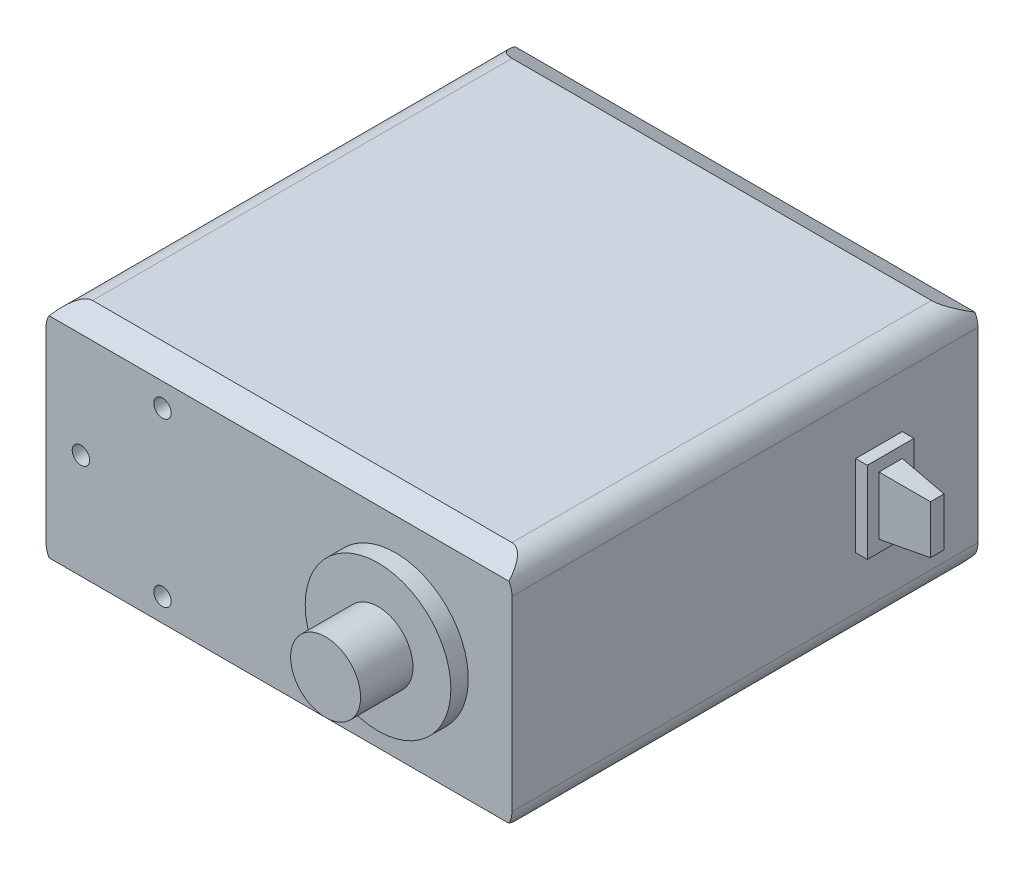
SolidWorks part; units mm, degrees
ref_plane "Спереди" through (0, 0, 0) normal (0, 0, 1) x (1, 0, 0)
ref_plane "Сверху" through (0, 0, 0) normal (0, 1, 0) x (1, 0, 0)
ref_plane "Справа" through (0, 0, 0) normal (1, 0, 0) x (0, 0, -1)
sketch "Эскиз1" plane through (0, 0, 0) normal (0, 1, 0) x (1, 0, 0)
  line L0 (0, 0) -> (40, 0)
  line L1 (40, 0) -> (40, -40)
  line L2 (40, -40) -> (0, -40)
  line L3 (0, -40) -> (0, 0)
extrude "Бобышка-Вытянуть1" add sketch "Эскиз1" along normal blind 20
sketch "Эскиз2" plane through (0, 0, 40) normal (0, 0, 1) x (1, 0, 0)
  line L0 (40, 10) -> (36.25, 10) construction
  line L1 (40, 20) -> (40, 0) construction
  line L2 (0, 10) -> (23.75, 10) construction
  line L3 (0, 20) -> (0, 0) construction
  line L4 (36.25, 10) -> (23.75, 10) construction
  circle A0 centre (30, 10) radius 6.25
  dimension "D1" = 12.5
  dimension "D2" = 3.75
extrude "Бобышка-Вытянуть2" add sketch "Эскиз2" along normal blind 1.5
sketch "Эскиз3" plane through (0, 0, 41.5) normal (0, 0, 1) x (1, 0, 0)
  circle A0 centre (30, 10) radius 3
extrude "Шестерня" add sketch "Эскиз3" along normal blind 4.5
sketch "Эскиз4" plane through (0, 0, 0) normal (0, 0, -1) x (-1, 0, 0)
  circle A0 centre (-30, 10) radius 6.25
extrude "Бобышка-Вытянуть4" add sketch "Эскиз4" along normal blind 1.5
sketch "Эскиз5" plane through (0, 0, -1.5) normal (0, 0, -1) x (-1, 0, 0)
  circle A0 centre (-30, 10) radius 3
extrude "Бобышка-Вытянуть5" add sketch "Эскиз5" along normal blind 3.7
sketch "Эскиз7" plane through (0, 0, 0) normal (0, 0, -1) x (-1, 0, 0)
  line L0 (0, 20) -> (-20, 0) construction
  line L1 (-40, 0) -> (0, 0) construction
  line L2 (0, 0) -> (-20, 20) construction
  line L3 (-40, 20) -> (0, 20) construction
  line L4 (0, 10.2204) -> (-2.5, 10.2204) construction
  line L5 (0, 20) -> (0, 0) construction
  line L6 (-2.5, 10.2204) -> (-2.5, 17.5) construction
  line L7 (-2.5, 10.2204) -> (-2.5, 2.5) construction
  line L8 (-2.5, 2.5) -> (-17.5, 2.5) construction
  line L9 (-17.5, 2.5) -> (-17.5, 17.5) construction
  line L10 (-17.5, 17.5) -> (-2.5, 17.5) construction
  circle A0 centre (-17.5, 17.5) radius 0.75
  circle A1 centre (-2.5, 17.5) radius 0.75
  circle A2 centre (-2.5, 2.5) radius 0.75
  circle A3 centre (-17.5, 2.5) radius 0.75
extrude "Вырез-Вытянуть1" cut sketch "Эскиз7" against normal blind 5
sketch "Эскиз8" plane through (0, 0, 40) normal (0, 0, 1) x (1, 0, 0)
  line L0 (2.5, 17.5) -> (17.5, 2.5) construction
  line L1 (17.5, 17.5) -> (2.5, 2.5) construction
  line L2 (10, 10) -> (10, 17) construction
  line L3 (10, 10) -> (3, 10) construction
  line L4 (10, 10) -> (10, 3) construction
  circle A0 centre (10, 17) radius 0.75
  circle A2 centre (3, 10) radius 0.75
  circle A3 centre (10, 3) radius 0.75
extrude "Вырез-Вытянуть2" cut sketch "Эскиз8" against normal blind 5
sketch "Эскиз9" plane through (40, 0, 0) normal (1, 0, 0) x (0, 0, -1)
  line L0 (0, 10) -> (-6.5, 10) construction
  line L1 (0, 20) -> (0, 0) construction
  line L2 (1.5, 10) -> (0, 10) construction
  line L3 (5.2, 10) -> (1.5, 10) construction
  line L4 (-6.5, 10) -> (-6.5, 13.5)
  line L5 (-6.5, 13.5) -> (-10.5, 13.5)
  line L6 (-10.5, 13.5) -> (-10.5, 6.5)
  line L7 (-10.5, 6.5) -> (-6.5, 6.5)
  line L8 (-6.5, 6.5) -> (-6.5, 10)
extrude "Бобышка-Вытянуть6" add sketch "Эскиз9" along normal blind 1
sketch "Эскиз10" plane through (41, 0, 0) normal (1, 0, 0) x (0, 0, -1)
  line L0 (-8.5, 13.5) -> (-8.5, 12.5)
  line L1 (-6.5, 13.5) -> (-10.5, 13.5) construction
  line L2 (-8.5, 12.5) -> (-9.5, 12.5)
  line L3 (-9.5, 12.5) -> (-9.5, 7.5)
  line L4 (-9.5, 7.5) -> (-7.5, 7.5)
  line L5 (-7.5, 12.5) -> (-8.5, 12.5)
  line L6 (-7.5, 12.5) -> (-7.5, 7.5)
extrude "Проводка" add sketch "Эскиз10" along normal blind 4 draft 6 contours L6 L5 L2 L3 L4
sketch "Эскиз11" plane through (40, 0, 0) normal (1, 0, 0) x (0, 0, -1)
  line L0 (-40, 20) -> (-38, 20)
  line L1 (-40, 20) -> (0, 20) construction
  line L2 (-40, 20) -> (-40, 19)
  line L3 (-40, 20) -> (-40, 0) construction
  line L4 (-40, 19) -> (-38, 20)
  line L5 (0, 20) -> (-2, 20)
  line L6 (0, 20) -> (0, 19)
  line L7 (0, 20) -> (0, 0) construction
  line L8 (0, 19) -> (-2, 20)
  line L9 (0, 0) -> (-2, 0)
  line L10 (-40, 0) -> (0, 0) construction
  line L11 (0, 0) -> (0, 1)
  line L12 (0, 1) -> (-2, 0)
  line L13 (-40, 0) -> (-38, 0)
  line L14 (-40, 0) -> (-40, 1)
  line L15 (-40, 1) -> (-38, 0)
extrude "Вырез-Вытянуть3" cut sketch "Эскиз11" against normal through all
sketch "Эскиз12" plane through (0, 0, 40) normal (0, 0, 1) x (1, 0, 0)
  line L0 (0, 20) -> (2, 20)
  line L1 (0, 20) -> (40, 20) construction
  line L2 (2, 20) -> (0, 19)
  line L3 (0, 19) -> (0, 20)
  line L4 (40, 20) -> (38, 20)
  line L5 (38, 20) -> (40, 19)
  line L6 (40, 19) -> (40, 20)
  line L7 (40, 0) -> (38, 0)
  line L8 (0, 0) -> (40, 0) construction
  line L9 (38, 0) -> (40, 1)
  line L10 (40, 1) -> (40, 0)
  line L11 (0, 0) -> (2, 0)
  line L12 (2, 0) -> (0, 1)
  line L13 (0, 1) -> (0, 0)
fillet "Скругление1" radius 2 4 edges at (0, 0, 20) (0, 20, 20) (40, 0, 20) (40, 20, 20)
